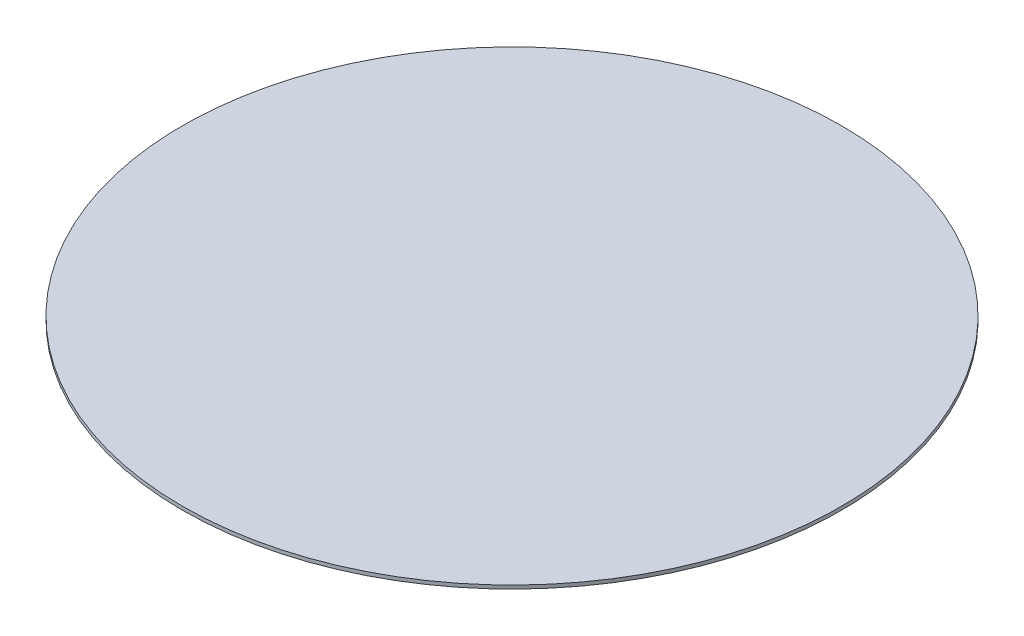
SolidWorks part; units mm, degrees
ref_plane "Front Plane" through (0, 0, 0) normal (0, 0, 1) x (1, 0, 0)
ref_plane "Top Plane" through (0, 0, 0) normal (0, 1, 0) x (1, 0, 0)
ref_plane "Right Plane" through (0, 0, 0) normal (1, 0, 0) x (0, 0, -1)
sketch "Sketch1" plane through (0, 0, 0) normal (0, 1, 0) x (1, 0, 0)
  circle A0 centre (0, 0) radius 149.225
  dimension "D1" = 298.45
extrude "Boss-Extrude1" add sketch "Sketch1" along normal blind 1.5875
equation "\"D1@Sketch1\"=11.75in"
